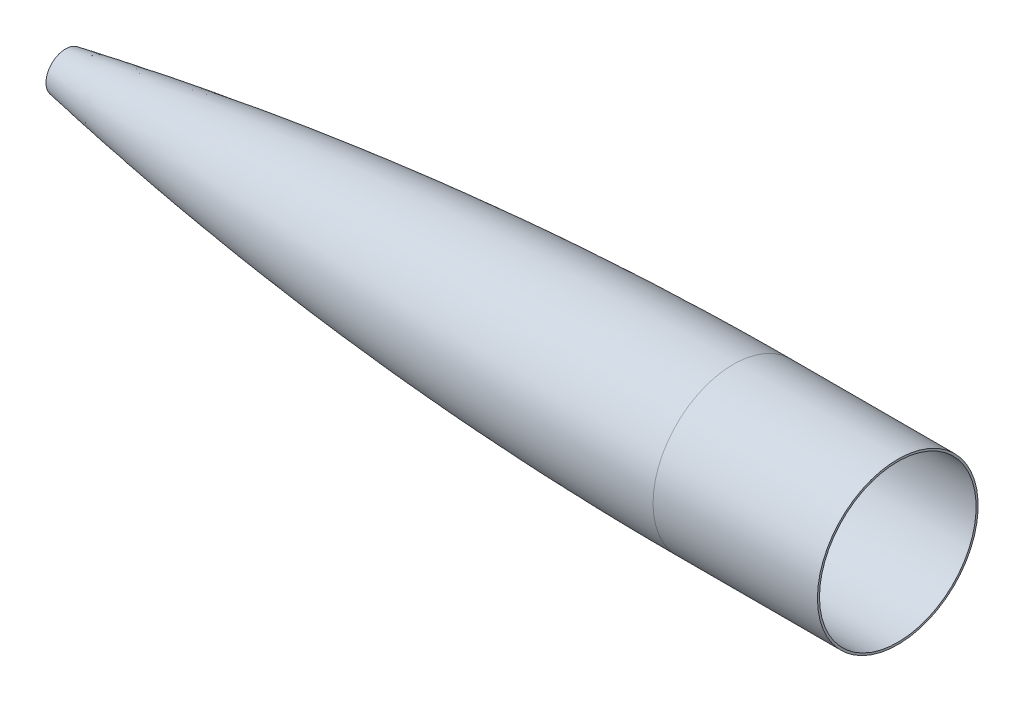
SolidWorks part; units mm, degrees
material "Thornel Mat VMA"
ref_plane "Front" through (0, 0, 0) normal (0, 0, 1) x (1, 0, 0)
ref_plane "Top" through (0, 0, 0) normal (0, 1, 0) x (1, 0, 0)
ref_plane "Right" through (0, 0, 0) normal (1, 0, 0) x (0, 0, -1)
sketch "Sketch3" plane through (0, 0, 0) normal (0, 0, 1) x (1, 0, 0)
  line L0 (0, 0) -> (814.8794, 0) construction
  line L1 (100, 18.9803) -> (100, 0)
  line L4 (749.9418, 78.2) -> (909.9418, 78.2)
  line L5 (909.9418, 78.2) -> (909.9418, 0)
  line L6 (909.9418, 0) -> (100, 0)
  spline S0 degree 4 poles (36.3123, 6.7544) (37.6526, 7.0241) (40.3338, 7.5622) (44.3595, 8.366) (49.7204, 9.4281) (55.0725, 10.4798) (60.3766, 11.5143) (65.7059, 12.5448) (70.9206, 13.5461) (76.3139, 14.572) (81.366, 15.5275) (87.0856, 16.5968) (91.5031, 17.4202) (98.1533, 18.6431) (101.17, 19.1948) (106.0332, 20.0784) (109.3625, 20.6791) (112.5998, 21.2603) (115.8617, 21.8432) (119.7195, 22.5288) (125.1904, 23.4939) (131.8191, 24.6522) (139.59, 25.9935) (148.5122, 27.5108) (157.4851, 29.0135) (166.4625, 30.494) (175.4431, 31.9519) (184.4277, 33.3874) (193.4156, 34.8004) (202.4071, 36.1908) (211.4021, 37.5588) (220.4004, 38.9043) (233.9029, 40.8887) (254.1691, 43.7808) (294.7393, 49.2944) (389.5801, 60.8164) (489.3054, 69.6518) (589.2632, 75.1541) (668.8474, 77.2741) (692.7268, 77.7109) (705.8044, 77.8901) (710.3533, 77.9458) (713.7404, 77.9845) (717.1031, 78.0201) (721.0099, 78.0574) (725.4618, 78.0945) (729.9059, 78.1261) (734.3824, 78.1524) (738.7927, 78.1731) (743.145, 78.1883) (748.7548, 78.1996) (751.826, 78.2022) (758.6023, 78.2013) (763.1037, 78.1898) (768.9383, 78.1716) (774.0903, 78.1448) (779.5941, 78.1104) (784.9156, 78.0678) (790.3565, 78.0171) (795.7726, 77.9581) (801.2396, 77.8906) (806.7169, 77.8145) (810.8312, 77.7512) (813.5719, 77.7063) (814.9421, 77.6832) knots 0 0 0 0 0 0.006983 0.013966 0.020949 0.027932 0.034788 0.041645 0.048502 0.055359 0.062215 0.069072 0.075929 0.082786 0.088468 0.09415 0.096991 0.099832 0.105514 0.111196 0.116878 0.128242 0.139856 0.151471 0.163085 0.174699 0.186314 0.197928 0.209543 0.221157 0.232772 0.244386 0.256 0.290844 0.337301 0.453445 0.743806 0.801878 0.848336 0.85995 0.865757 0.868661 0.871564 0.877246 0.882928 0.88861 0.894293 0.899975 0.905657 0.911339 0.917021 0.923893 0.930766 0.937639 0.944512 0.951385 0.958257 0.96513 0.972003 0.979002 0.986001 0.993001 1 1 1 1 1 construction
  spline S1 degree 4 poles (100, 18.9803) (100.9132, 19.1471) (102.7533, 19.4825) (106.0332, 20.0784) (109.3625, 20.6791) (112.5998, 21.2603) (115.8617, 21.8432) (119.7195, 22.5288) (125.1904, 23.4939) (131.8191, 24.6522) (139.59, 25.9935) (148.5122, 27.5108) (157.4851, 29.0135) (166.4625, 30.494) (175.4431, 31.9519) (184.4277, 33.3874) (193.4156, 34.8004) (202.4071, 36.1908) (211.4021, 37.5588) (220.4004, 38.9043) (233.9029, 40.8887) (254.1691, 43.7808) (294.7393, 49.2944) (389.5801, 60.8164) (489.3054, 69.6518) (589.2632, 75.1541) (668.8474, 77.2741) (692.7268, 77.7109) (705.8044, 77.8901) (710.3533, 77.9458) (713.7404, 77.9845) (717.1031, 78.0201) (721.0099, 78.0574) (725.4618, 78.0945) (729.9059, 78.1261) (734.3824, 78.1524) (738.7927, 78.1731) (743.145, 78.1883) (747.1429, 78.1963) (749.0134, 78.1991) (749.9418, 78.2) knots 0.082786 0.082786 0.082786 0.082786 0.082786 0.088468 0.09415 0.096991 0.099832 0.105514 0.111196 0.116878 0.128242 0.139856 0.151471 0.163085 0.174699 0.186314 0.197928 0.209543 0.221157 0.232772 0.244386 0.256 0.290844 0.337301 0.453445 0.743806 0.801878 0.848336 0.85995 0.865757 0.868661 0.871564 0.877246 0.882928 0.88861 0.894293 0.899975 0.905657 0.911339 0.917021 0.917021 0.917021 0.917021 0.917021
  dimension "D1" = 160
  dimension "D2" = 78.2
  dimension "D3" = 100
  dimension "D4" = 18.9803
revolve "Revolve2" add sketch "Sketch3" angle 360 about L0
shell "Shell1" thickness 2
